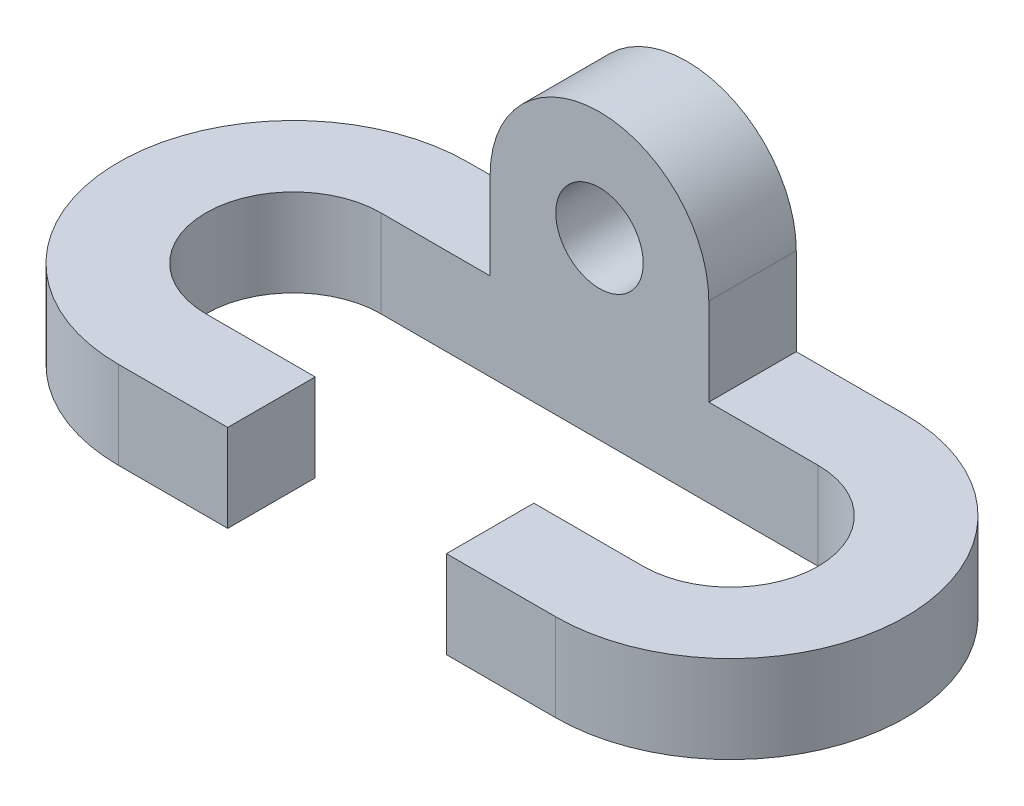
SolidWorks part; units mm, degrees
ref_plane "Front Plane" through (0, 0, 0) normal (0, 0, 1) x (1, 0, 0)
ref_plane "Top Plane" through (0, 0, 0) normal (0, 1, 0) x (1, 0, 0)
ref_plane "Right Plane" through (0, 0, 0) normal (1, 0, 0) x (0, 0, -1)
sketch "Sketch3" plane through (0, 0, 0) normal (0, 1, 0) x (1, 0, 0)
  line L1 (0, 0) -> (-63.5, 0)
  line L3 (0, 50.8) -> (-63.5, 50.8)
  arc A0 (-63.5, 50.8) -> (-63.5, 0) centre (-63.5, 25.4) ccw
  arc A1 (0, 50.8) -> (0, 0) centre (0, 25.4) cw
  dimension "D3" = 25.4
  dimension "D1" = 63.5
  dimension "D2" = 50.8
extrude "Boss-Extrude2" add sketch "Sketch3" along normal blind 12.7
hole_wizard "1 (1) Diameter Hole1" positions "Sketch4" profile "Sketch5" hole size "1" standard "ANSI Inch" end condition through all
sketch "Sketch4" plane through (0, 12.7, 0) normal (0, 1, 0) x (1, 0, 0)
  line L0 (-63.5, 0) -> (0, 0) construction
  arc A0 (-63.5, 50.8) -> (-63.5, 0) centre (-63.5, 25.4) ccw construction
  arc A1 (0, 0) -> (0, 50.8) centre (0, 25.4) ccw construction
  point P0 (-63.5, 25.4)
  point P2 (0, 25.4)
  dimension "D1" = 0
  dimension "D2" = 0
  dimension "D3" = 25.4
  dimension "D4" = 25.4
sketch "Sketch5" plane through (-63.5, 12.7, -25.4) normal (1, 0, 0) x (0, 0, 1)
  line L0 (0, 0) -> (0, 12.7)
  line L1 (0, 12.7) -> (12.7, 12.7)
  line L2 (12.7, 12.7) -> (12.7, 0)
  line L5 (12.7, 0) -> (0, 0)
  line L11 (0, -6.35) -> (0, 107.95) construction
  dimension "Thru Hole Dia." = 25.4
  dimension "Thru Hole Depth" = 12.7
sketch "Sketch6" plane through (0, 12.7, 0) normal (0, 1, 0) x (1, 0, 0)
  line L1 (-63.5, 38.1) -> (0, 38.1)
  line L2 (-63.5, 38.1) -> (-63.5, 12.7)
  line L3 (-63.5, 12.7) -> (0, 12.7)
  line L4 (0, 38.1) -> (0, 12.7)
  circle A0 centre (-63.5, 25.4) radius 12.7 construction
  circle A1 centre (0, 25.4) radius 12.7 construction
extrude "Cut-Extrude1" cut sketch "Sketch6" against normal blind 12.7
sketch "Sketch7" plane through (0, 0, 0) normal (0, 0, 1) x (1, 0, 0)
  line L0 (-63.5, 12.7) -> (0, 12.7) construction
  line L1 (-47.625, 12.7) -> (-15.875, 12.7)
  line L2 (-47.625, 12.7) -> (-47.625, 0)
  line L3 (-47.625, 0) -> (-15.875, 0)
  line L4 (-15.875, 12.7) -> (-15.875, 0)
  line L5 (-63.5, 0) -> (0, 0) construction
  line L6 (-63.5, 12.7) -> (-63.5, 0) construction
  line L7 (0, 12.7) -> (0, 0) construction
  dimension "D1" = 31.75
  dimension "D2" = 15.875
  dimension "D3" = 15.875
extrude "Cut-Extrude2" cut sketch "Sketch7" against normal blind 12.7
sketch "Sketch8" plane through (0, 12.7, 0) normal (0, 1, 0) x (1, 0, 0)
  line L0 (0, 38.1) -> (-63.5, 38.1) construction
  line L1 (-47.625, 38.1) -> (-15.875, 38.1)
  line L2 (-47.625, 38.1) -> (-47.625, 50.8)
  line L3 (-47.625, 50.8) -> (-15.875, 50.8)
  line L4 (-15.875, 38.1) -> (-15.875, 50.8)
  line L5 (0, 50.8) -> (-63.5, 50.8) construction
  line L6 (-47.625, 12.7) -> (-47.625, 0) construction
  dimension "D1" = 31.75
  dimension "D2" = 0
extrude "Boss-Extrude3" add sketch "Sketch8" along normal blind 28.575
hole_wizard "1/2 (0.5) Diameter Hole1" positions "Sketch9" profile "Sketch10" hole size "1/2" standard "ANSI Inch" end condition through all
sketch "Sketch9" plane through (0, 0, -38.1) normal (0, 0, 1) x (1, 0, 0)
  line L0 (0, 0) -> (-63.5, 0) construction
  line L2 (-15.875, 41.275) -> (-15.875, 12.7) construction
  point P0 (-31.75, 25.4)
  point P9 (-61.5751, 39.4122)
  dimension "D1" = 25.4
  dimension "D2" = 15.875
sketch "Sketch10" plane through (-31.75, 25.4, -38.1) normal (1, 0, 0) x (0, -1, 0)
  line L0 (0, 0) -> (0, 12.7)
  line L1 (0, 12.7) -> (6.35, 12.7)
  line L2 (6.35, 12.7) -> (6.35, 0)
  line L5 (6.35, 0) -> (0, 0)
  line L11 (0, -6.35) -> (0, 107.95) construction
  dimension "Thru Hole Dia." = 12.7
  dimension "Thru Hole Depth" = 12.7
sketch "Sketch12" plane through (0, 0, -38.1) normal (0, 0, 1) x (1, 0, 0)
  line L1 (-47.625, 41.275) -> (-47.625, 12.7) construction
  line L2 (-15.875, 41.275) -> (-15.875, 12.7) construction
  line L4 (-47.625, 41.275) -> (-15.875, 41.275)
  line L5 (-47.625, 41.275) -> (-47.625, 25.4)
  line L7 (-15.875, 41.275) -> (-15.875, 25.4)
  arc A0 (-47.625, 25.4) -> (-15.875, 25.4) centre (-31.75, 25.4) cw
  line M5 (-15.875, 12.7) -> (-15.875, 41.275)
  line M6 (-15.875, 41.275) -> (-47.625, 41.275)
  line M7 (-47.625, 41.275) -> (-47.625, 12.7)
extrude "Cut-Extrude4" cut sketch "Sketch12" against normal blind 12.7 contours A0 L4 M7 | A0 M6 M5
